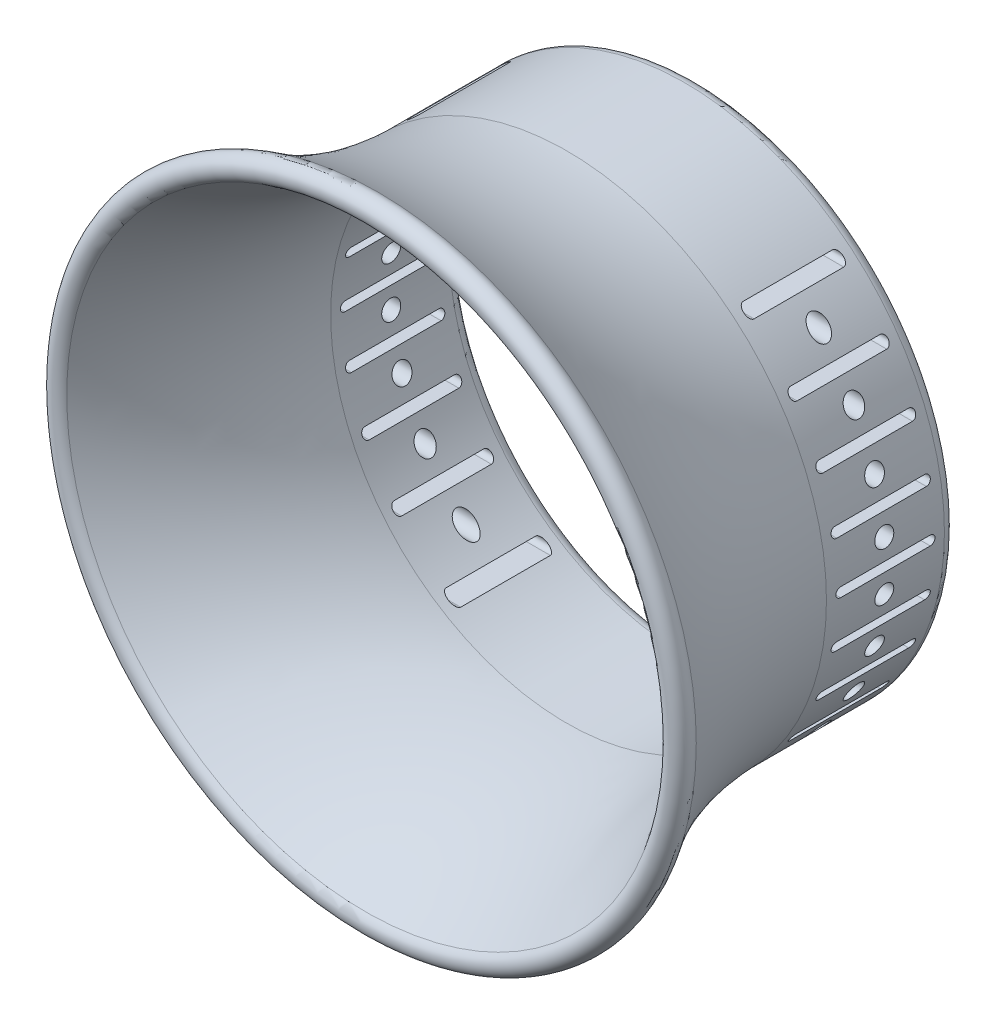
SolidWorks part; units mm, degrees
other "Markup1"
sketch "Sketch2" plane through (-67.8261, 67.8261, 51.0537) normal (-0.7784, 0.528, 0.3396) x (0.4925, 0.1782, 0.8519)
ref_plane "Front Plane" through (0, 0, 0) normal (0, 0, 1) x (1, 0, 0)
ref_plane "Top Plane" through (0, 0, 0) normal (0, 1, 0) x (1, 0, 0)
ref_plane "Right Plane" through (0, 0, 0) normal (1, 0, 0) x (0, 0, -1)
sketch "Sketch1" plane through (0, 0, 0) normal (1, 0, 0) x (0, 0, -1)
  line L0 (-41.2359, 0) -> (64.2513, 0) construction
  line L1 (17.8184, 55) -> (-7.1816, 55)
  line L2 (17.8184, 50) -> (-7.2465, 50)
  arc A1 (17.8184, 55) -> (17.8184, 50) centre (17.8184, 52.5) cw
  arc A2 (-49.9258, 63.2363) -> (-47.1816, 67.4159) centre (-48.5537, 65.3261) cw
  spline S0 degree 2 poles (-7.1816, 55) (-29.1402, 55.5706) (-47.1816, 67.4159) knots 0 0 0 1 1 1
  spline S1 degree 1 poles (-7.2465, 50) (-49.9258, 63.2363) knots 0 0 1 1 construction
  spline S2 degree 2 poles (-7.2465, 50) (-15.9833, 50.2175) (-29.676, 53.4149) (-42.724, 58.5055) (-49.9258, 63.2363) knots -0.001478 -0.001478 -0.001478 0.374076 0.624446 1 1 1
  dimension "D1" = 5
  dimension "D2" = 50
  dimension "D3" = 60
  dimension "D4" = 25
  dimension "D5" = 40
revolve "Revolve1" add sketch "Sketch1" angle 360 about L0
ref_plane "Plane1" through (60, 0, 0) normal (1, 0, 0) x (0, 0, -1)
sketch "Sketch4" plane through (60, 0, 0) normal (1, 0, 0) x (0, 0, -1)
  line L0 (5.3184, 0) -> (5.3184, -91.7618) construction
  line L1 (17.8184, 55) -> (17.8184, -55) construction
  line L2 (5.3184, -21.8827) -> (5.3184, 72.8594) construction
  line L3 (-4.1816, 10.5) -> (14.8184, 10.5) construction
  line L4 (37.0678, 0) -> (-88.6843, 0) construction
  line L5 (17.8184, 55) -> (-7.1816, 55) construction
  line L6 (-4.1816, 0) -> (14.8184, 0) construction
  line L7 (-4.1816, 1) -> (14.8184, 1)
  line L8 (-4.1816, -1) -> (14.8184, -1)
  line L9 (-4.1816, 11.5) -> (14.8184, 11.5)
  line L10 (-4.1816, 9.5) -> (14.8184, 9.5)
  line L11 (-4.1816, 21) -> (14.8184, 21) construction
  line L12 (-4.1816, 22) -> (14.8184, 22)
  line L13 (-4.1816, 20) -> (14.8184, 20)
  line L14 (-4.1816, 31.5) -> (14.8184, 31.5) construction
  line L15 (-4.1816, 32.5) -> (14.8184, 32.5)
  line L16 (-4.1816, 30.5) -> (14.8184, 30.5)
  line L17 (-4.1816, 42) -> (14.8184, 42) construction
  line L18 (-4.1816, 43) -> (14.8184, 43)
  line L19 (-4.1816, 41) -> (14.8184, 41)
  line L20 (-4.1816, -10.5) -> (14.8184, -10.5) construction
  line L21 (-4.1816, -11.5) -> (14.8184, -11.5)
  line L22 (-4.1816, -9.5) -> (14.8184, -9.5)
  line L23 (-4.1816, -21) -> (14.8184, -21) construction
  line L24 (-4.1816, -22) -> (14.8184, -22)
  line L25 (-4.1816, -20) -> (14.8184, -20)
  line L26 (-4.1816, -31.5) -> (14.8184, -31.5) construction
  line L27 (-4.1816, -32.5) -> (14.8184, -32.5)
  line L28 (-4.1816, -30.5) -> (14.8184, -30.5)
  line L29 (-4.1816, -42) -> (14.8184, -42) construction
  line L30 (-4.1816, -43) -> (14.8184, -43)
  line L31 (-4.1816, -41) -> (14.8184, -41)
  arc A0 (-4.1816, 1) -> (-4.1816, -1) centre (-4.1816, 0) ccw
  arc A1 (14.8184, -1) -> (14.8184, 1) centre (14.8184, 0) ccw
  arc A2 (-4.1816, 11.5) -> (-4.1816, 9.5) centre (-4.1816, 10.5) ccw
  arc A3 (14.8184, 9.5) -> (14.8184, 11.5) centre (14.8184, 10.5) ccw
  arc A4 (-4.1816, 22) -> (-4.1816, 20) centre (-4.1816, 21) ccw
  arc A5 (14.8184, 20) -> (14.8184, 22) centre (14.8184, 21) ccw
  arc A6 (-4.1816, 32.5) -> (-4.1816, 30.5) centre (-4.1816, 31.5) ccw
  arc A7 (14.8184, 30.5) -> (14.8184, 32.5) centre (14.8184, 31.5) ccw
  arc A8 (-4.1816, 43) -> (-4.1816, 41) centre (-4.1816, 42) ccw
  arc A9 (14.8184, 41) -> (14.8184, 43) centre (14.8184, 42) ccw
  arc A10 (-4.1816, -11.5) -> (-4.1816, -9.5) centre (-4.1816, -10.5) cw
  arc A11 (14.8184, -9.5) -> (14.8184, -11.5) centre (14.8184, -10.5) cw
  arc A12 (-4.1816, -22) -> (-4.1816, -20) centre (-4.1816, -21) cw
  arc A13 (14.8184, -20) -> (14.8184, -22) centre (14.8184, -21) cw
  arc A14 (-4.1816, -32.5) -> (-4.1816, -30.5) centre (-4.1816, -31.5) cw
  arc A15 (14.8184, -30.5) -> (14.8184, -32.5) centre (14.8184, -31.5) cw
  arc A16 (-4.1816, -43) -> (-4.1816, -41) centre (-4.1816, -42) cw
  arc A17 (14.8184, -41) -> (14.8184, -43) centre (14.8184, -42) cw
  point P11 (5.3184, 0)
  point P21 (5.3184, 10.5)
  point P28 (5.3184, 21)
  point P35 (5.3184, 31.5)
  point P42 (5.3184, 42)
  point P47 (5.3184, -10.5)
  point P54 (5.3184, -21)
  point P61 (5.3184, -31.5)
  point P68 (5.3184, -42)
  dimension "D1" = 12.5
  dimension "D2" = 55
  dimension "D3" = 2
  dimension "D4" = 19
  dimension "D5" = 5
extrude "Cut-Extrude2" cut sketch "Sketch4" against normal through all both and the other way through all
sketch "Sketch5" plane through (60, 0, 0) normal (1, 0, 0) x (0, 0, -1)
  line L0 (17.8184, 55) -> (17.8184, -55) construction
  line L1 (14.8184, -1) -> (-4.1816, -1) construction
  line L2 (5.3184, -61.9336) -> (5.3184, 57.6311) construction
  circle A0 centre (5.3184, -5.25) radius 2.006
  circle A1 centre (5.3184, 5.25) radius 2.006
  circle A2 centre (5.3184, 15.75) radius 2.006
  circle A3 centre (5.3184, 26.25) radius 2.006
  circle A4 centre (5.3184, 36.75) radius 2.006
  circle A6 centre (5.3184, -15.75) radius 2.006
  circle A7 centre (5.3184, -26.25) radius 2.006
  circle A8 centre (5.3184, -36.75) radius 2.006
  circle A10 centre (5.3184, 47.25) radius 2.006 [skipped]
  circle A11 centre (5.3184, -47.25) radius 2.006 [skipped]
  dimension "D1" = 12.5
  dimension "D2" = 4.25
  dimension "D3" = 6
  dimension "D4" = 5
extrude "Cut-Extrude3" cut sketch "Sketch5" against normal through all both
